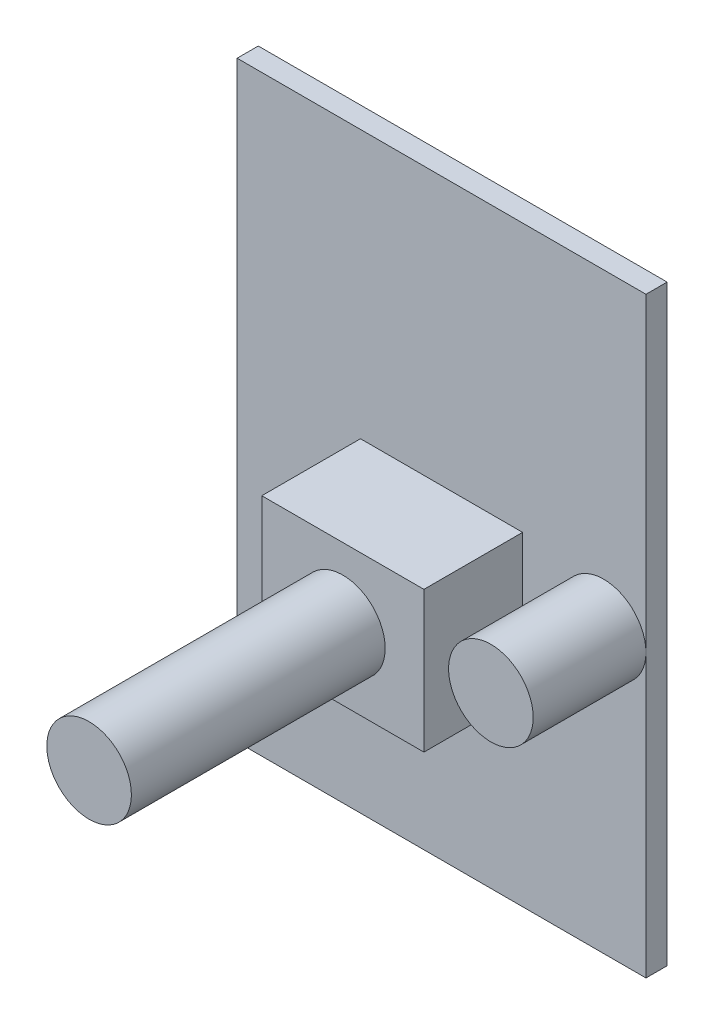
SolidWorks part; units mm, degrees
ref_plane "Front Plane" through (0, 0, 0) normal (0, 0, 1) x (1, 0, 0)
ref_plane "Top Plane" through (0, 0, 0) normal (0, 1, 0) x (1, 0, 0)
ref_plane "Right Plane" through (0, 0, 0) normal (1, 0, 0) x (0, 0, -1)
sketch "Sketch1" plane through (0, 0, 0) normal (0, 0, 1) x (1, 0, 0)
  line L1 (-14.5, 21) -> (14.5, 21)
  line L2 (-14.5, 21) -> (-14.5, -21)
  line L3 (-14.5, -21) -> (14.5, -21)
  line L4 (14.5, 21) -> (14.5, -21)
  line L5 (-14.5, 21) -> (14.5, -21) construction
  line L6 (-14.5, -21) -> (14.5, 21) construction
  point P0 (0, 0)
  dimension "D1" = 42
  dimension "D2" = 29
extrude "Boss-Extrude1" add sketch "Sketch1" along normal blind 1.5
sketch "Sketch2" plane through (0, 0, 1.5) normal (0, 0, 1) x (1, 0, 0)
  line L0 (0, 0) -> (0, -3) construction
  line L1 (-14.5, -21) -> (14.5, -21) construction
  line L2 (-5.75, 2) -> (5.75, 2)
  line L3 (-5.75, 2) -> (-5.75, -8)
  line L4 (-5.75, -8) -> (5.75, -8)
  line L5 (5.75, 2) -> (5.75, -8)
  line L6 (-5.75, 2) -> (5.75, -8) construction
  line L7 (-5.75, -8) -> (5.75, 2) construction
  dimension "D1" = 10
  dimension "D2" = 11.5
  dimension "D3" = 18
extrude "Boss-Extrude2" add sketch "Sketch2" along normal blind 7
sketch "Sketch3" plane through (0, 0, 8.5) normal (0, 0, 1) x (1, 0, 0)
  line L0 (-5.75, -3) -> (5.75, -3) construction
  line L1 (-5.75, 2) -> (-5.75, -8) construction
  line L2 (5.75, -8) -> (5.75, 2) construction
  circle A0 centre (0, -3) radius 3
  dimension "D1" = 6
extrude "Boss-Extrude3" add sketch "Sketch3" along normal blind 18
sketch "Sketch4" plane through (0, 0, 1.5) normal (0, 0, 1) x (1, 0, 0)
  line L2 (5.75, 2) -> (-5.75, 2) construction
  line L3 (14.5, -21) -> (14.5, 21) construction
  circle A0 centre (11.5, -1) radius 3
  point P4 (10.2856, -1.09)
  dimension "D1" = 6
extrude "Boss-Extrude4" add sketch "Sketch4" along normal blind 8
